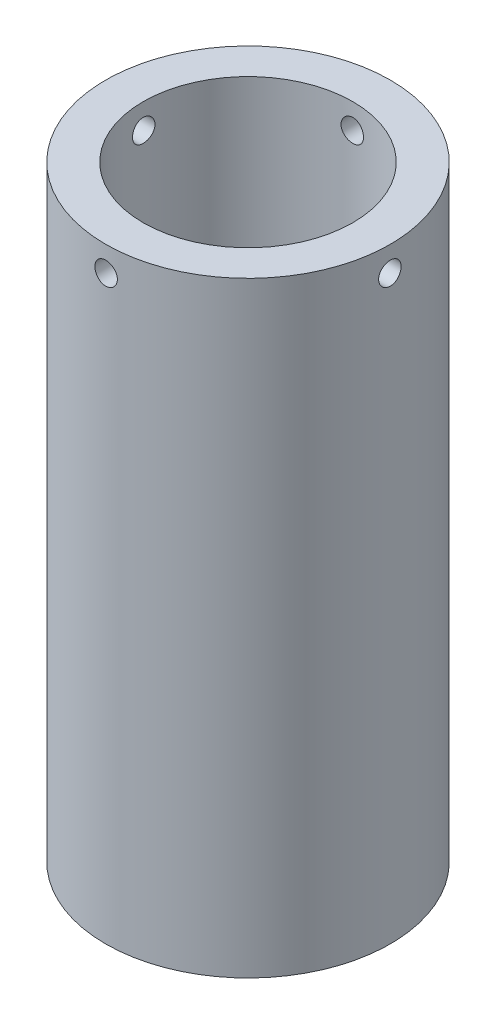
SolidWorks part; units mm, degrees
ref_plane "Front Plane" through (0, 0, 0) normal (0, 0, 1) x (1, 0, 0)
ref_plane "Top Plane" through (0, 0, 0) normal (0, 1, 0) x (1, 0, 0)
ref_plane "Right Plane" through (0, 0, 0) normal (1, 0, 0) x (0, 0, -1)
sketch "Sketch1" plane through (0, 0, 0) normal (0, 1, 0) x (1, 0, 0)
  circle A0 centre (0, 0) radius 28.5
  circle A1 centre (0, 0) radius 21
  dimension "D1" = 57
  dimension "D2" = 42
extrude "Boss-Extrude1" add sketch "Sketch1" along normal mid plane 121.35
sketch "Sketch2" plane through (0, 0, 0) normal (0, 0, 1) x (1, 0, 0)
  line L3 (21, 60.675) -> (-21, 60.675) construction
  circle A0 centre (0, 55.675) radius 2.25
  dimension "D1" = 4.5
  dimension "D2" = 5
extrude "Cut-Extrude1" cut sketch "Sketch2" against normal through all
pattern_circular "CirPattern1" count 4 every 90 about axis through (0, 60.675, 0) along (0, -1, 0) of "Cut-Extrude1"
sketch "Sketch3" plane through (0, -60.675, 0) normal (0, -1, 0) x (1, 0, 0)
  line L0 (0, 28.5) -> (0, 21) construction
  circle A0 centre (0, 0) radius 28.5 construction
  arc A1 (2.25, 20.8791) -> (-2.25, 20.8791) centre (0, 0) ccw construction
  circle A2 centre (0, 24.75) radius 2.25
  circle A3 centre (24.75, 0) radius 2.25
  circle A4 centre (0, -24.75) radius 2.25
  circle A5 centre (-24.75, 0) radius 2.25
  point P19 (0, 0)
  dimension "D1" = 4.5
  dimension "D2" = 4
extrude "Cut-Extrude2" cut sketch "Sketch3" against normal blind 6.5
